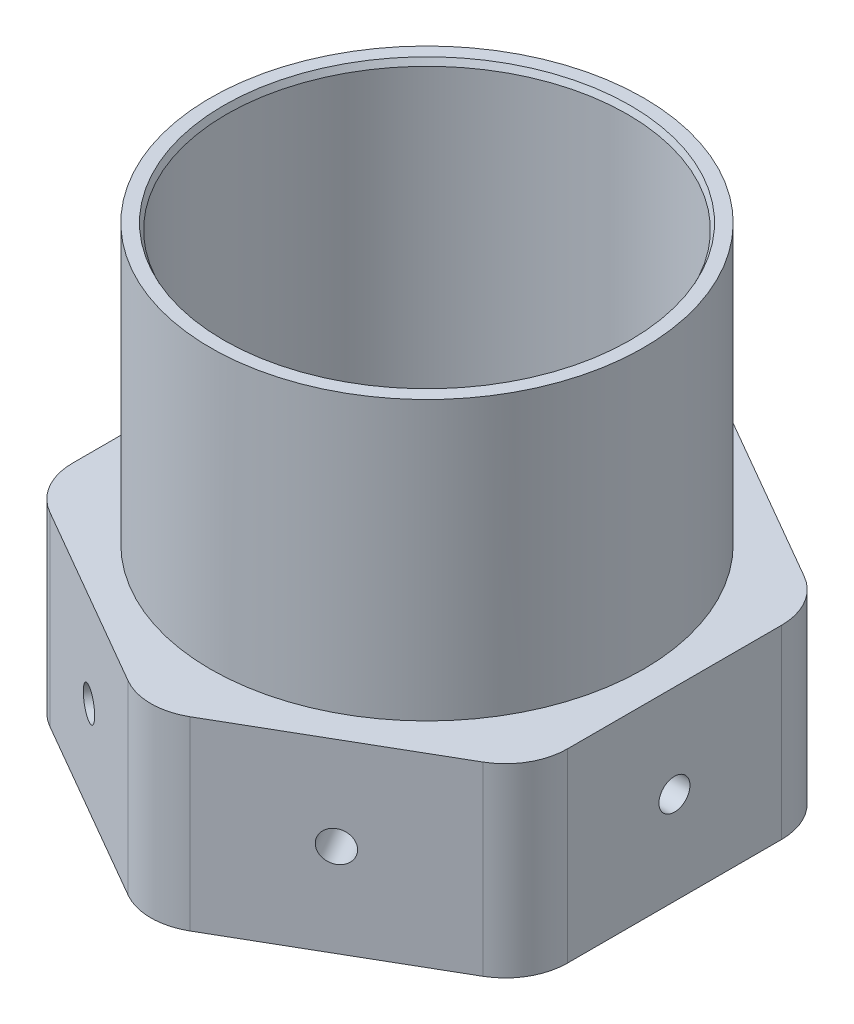
SolidWorks part; units mm, degrees
ref_plane "Front Plane" through (0, 0, 0) normal (0, 0, 1) x (1, 0, 0)
ref_plane "Top Plane" through (0, 0, 0) normal (0, 1, 0) x (1, 0, 0)
ref_plane "Right Plane" through (0, 0, 0) normal (1, 0, 0) x (0, 0, -1)
sketch "Sketch1" plane through (0, 0, 0) normal (0, 1, 0) x (1, 0, 0)
  line L9 (0, -58.6588) -> (50.8, -29.3294)
  line L10 (50.8, -29.3294) -> (50.8, 29.3294)
  line L11 (50.8, 29.3294) -> (0, 58.6588)
  line L12 (0, 58.6588) -> (-50.8, 29.3294)
  line L13 (-50.8, 29.3294) -> (-50.8, -29.3294)
  line L14 (-50.8, -29.3294) -> (0, -58.6588)
  circle A0 centre (0, 0) radius 41.148
  circle A1 centre (0, 0) radius 50.8 construction
  dimension "D1" = 101.6
  dimension "D2" = 82.296
extrude "Boss-Extrude1" add sketch "Sketch1" along normal blind 38.1
sketch "Sketch2" plane through (-50.8, 0, 0) normal (-1, 0, 0) x (0, 0, 1)
  circle A0 centre (0, 19.05) radius 3.1813
  dimension "D1" = 6.3627
extrude "Cut-Extrude1" cut sketch "Sketch2" against normal blind 29.464 contours A0
pattern_circular "CirPattern1" count 6 over 360 about axis through (0, 38.1, 0) along (0, 1, 0) of "Cut-Extrude1"
ref_plane "Plane1" through (-50.8, 38.1, -29.3294) normal (0, -1, 0) x (-1, 0, 0)
sketch "Sketch3" plane through (-50.8, 38.1, -29.3294) normal (0, -1, 0) x (1, 0, 0)
  circle A0 centre (50.8, 29.3294) radius 41.148
  circle A1 centre (50.8, 29.3294) radius 44.45
  circle A2 centre (50.8, 29.3294) radius 41.148 construction
  dimension "D1" = 88.9
extrude "Boss-Extrude2" add sketch "Sketch3" against normal blind 57.15
fillet "Fillet1" radius 12.7 6 edges at (-50.8, 19.05, -29.3294) (0, 19.05, -58.6588) (50.8, 19.05, -29.3294) (50.8, 19.05, 29.3294) (-50.8, 19.05, 29.3294) (0, 19.05, 58.6588)
chamfer "Chamfer1" distance 1.27 angle 25 2 edges at (0, 0, 41.148) (0, 95.25, -41.148)
